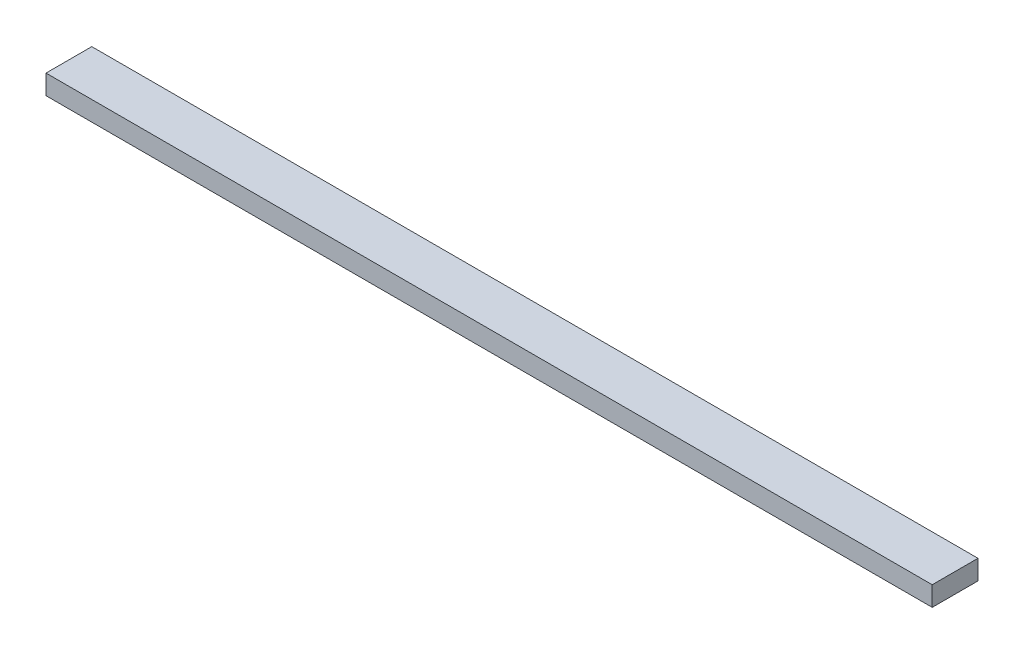
SolidWorks part; units mm, degrees
ref_plane "前视基准面" through (0, 0, 0) normal (0, 0, 1) x (1, 0, 0)
ref_plane "上视基准面" through (0, 0, 0) normal (0, 1, 0) x (1, 0, 0)
ref_plane "右视基准面" through (0, 0, 0) normal (1, 0, 0) x (0, 0, -1)
other "Configuration Table"
sketch "草图1" plane through (0, 0, 0) normal (0, 0, 1) x (1, 0, 0)
  line L1 (-67.75, -1.5) -> (67.75, -1.5)
  line L2 (-67.75, -1.5) -> (-67.75, 1.5)
  line L3 (-67.75, 1.5) -> (67.75, 1.5)
  line L4 (67.75, -1.5) -> (67.75, 1.5)
  line L5 (-67.75, -1.5) -> (67.75, 1.5) construction
  line L6 (-67.75, 1.5) -> (67.75, -1.5) construction
  point P0 (0, 0)
extrude "凸台-拉伸1" add sketch "草图1" along normal blind 7
